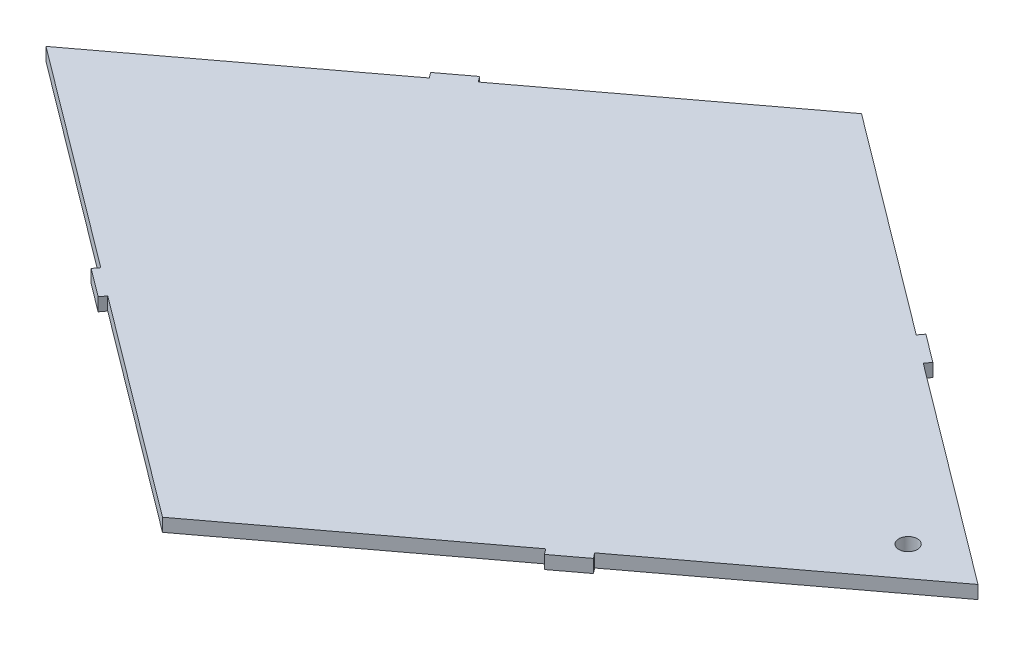
SolidWorks part; units mm, degrees
ref_plane "Front Plane" through (0, 0, 0) normal (0, 0, 1) x (1, 0, 0)
ref_plane "Top Plane" through (0, 0, 0) normal (0, 1, 0) x (1, 0, 0)
ref_plane "Right Plane" through (0, 0, 0) normal (1, 0, 0) x (0, 0, -1)
sketch "Sketch1" plane through (0, 0, 0) normal (0, 1, 0) x (1, 0, 0)
  line L0 (0, 150) -> (94, 79.5)
  line L1 (200, 0) -> (106, -70.5)
  line L2 (0, -150) -> (-94, -79.5)
  line L3 (-200, 0) -> (-106, 70.5)
  line L4 (-106, 70.5) -> (-107.77, 72.86)
  line L5 (-107.77, 72.86) -> (-95.77, 81.86)
  line L6 (-95.77, 81.86) -> (-94, 79.5)
  line L7 (-106, -70.5) -> (-107.77, -72.86)
  line L8 (-107.77, -72.86) -> (-95.77, -81.86)
  line L9 (-95.77, -81.86) -> (-94, -79.5)
  line L10 (94, -79.5) -> (95.77, -81.86)
  line L11 (95.77, -81.86) -> (107.77, -72.86)
  line L12 (107.77, -72.86) -> (106, -70.5)
  line L13 (94, -79.5) -> (0, -150)
  line L14 (-106, -70.5) -> (-200, 0)
  line L15 (-94, 79.5) -> (0, 150)
  line L16 (94, 79.5) -> (95.77, 81.86)
  line L17 (95.77, 81.86) -> (107.77, 72.86)
  line L18 (107.77, 72.86) -> (106, 70.5)
  line L19 (106, 70.5) -> (200, 0)
  circle A0 centre (170, 0) radius 4
  dimension "D18" = 8
  dimension "D1" = 400
  dimension "D2" = 300
  dimension "D3" = 15
  dimension "D4" = 2.95
  dimension "D6" = 15
  dimension "D7" = 2.95
  dimension "D10" = 15
  dimension "D11" = 2.95
  dimension "D5" = 15
  dimension "D8" = 2.95
  dimension "D12" = 200
  dimension "D13" = 150
  dimension "D9" = 250
  dimension "D14" = 117.5
  dimension "D15" = 117.5
  dimension "D16" = 117.5
  dimension "D17" = 117.5
  dimension "D19" = 30
extrude "Boss-Extrude1" add sketch "Sketch1" along normal blind 5.63
equation "\"Side\"= 170.5"
equation "\"thick acrylic\"= 5.63"
equation "\"connect width\"= 15"
equation "\"thin acrylic\"= 2.95"
equation "\"width\"= 300"
equation "\"length\"= 400"
equation "\"D2@Sketch1\"=\"width\""
equation "\"D3@Sketch1\"=\"connect width\""
equation "\"D4@Sketch1\"=\"thin acrylic\""
equation "\"D6@Sketch1\"=\"connect width\""
equation "\"D7@Sketch1\"=\"thin acrylic\""
equation "\"D10@Sketch1\"=\"connect width\""
equation "\"D11@Sketch1\"=\"thin acrylic\""
equation "\"D5@Sketch1\"=\"connect width\""
equation "\"D8@Sketch1\"=\"thin acrylic\""
equation "\"D12@Sketch1\"=\"length\"/2"
equation "\"D13@Sketch1\"=\"width\"/2"
equation "\"D14@Sketch1\"=(\"D9@Sketch1\"-\"connect width\")/2"
equation "\"D15@Sketch1\"=(\"D9@Sketch1\"-\"connect width\")/2"
equation "\"D16@Sketch1\"=(\"D9@Sketch1\"-\"connect width\")/2"
equation "\"D17@Sketch1\"=(\"D9@Sketch1\"-\"connect width\")/2"
equation "\"D1@Boss-Extrude1\"=\"thick acrylic\""
